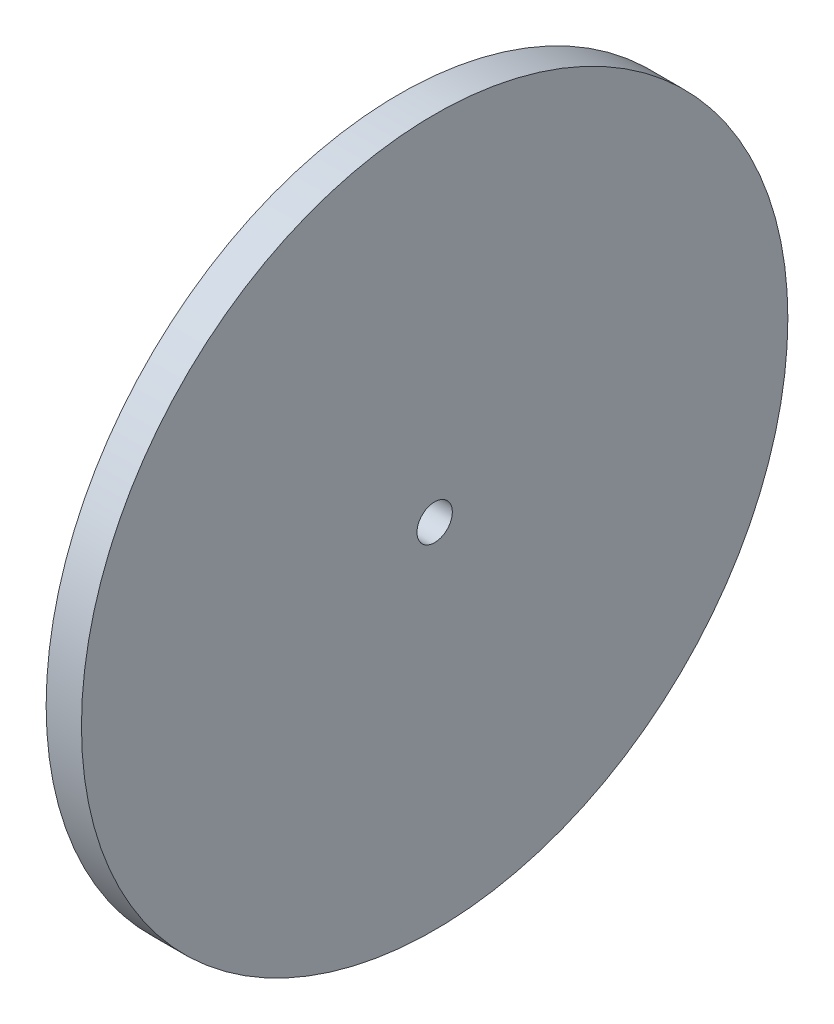
SolidWorks part; units mm, degrees
material "CMR DEFAULT - CHANGE MATERIAL"
ref_plane "XY PLANE - TOP" through (0, 0, 0) normal (0, 0, 1) x (1, 0, 0)
ref_plane "XZ PLANE - SIDE" through (0, 0, 0) normal (0, 1, 0) x (1, 0, 0)
ref_plane "YZ PLANE - FRONT" through (0, 0, 0) normal (1, 0, 0) x (0, 0, -1)
sketch "Sketch1" plane through (0, 0, 0) normal (1, 0, 0) x (0, 0, -1)
  circle A0 centre (0, 0) radius 63.5
  circle A1 centre (0, 0) radius 3.175
  point P10 (0, 0)
  dimension "D1" = 127
  dimension "D2" = 6.35
extrude "Boss-Extrude1" add sketch "Sketch1" along normal blind 6.35
